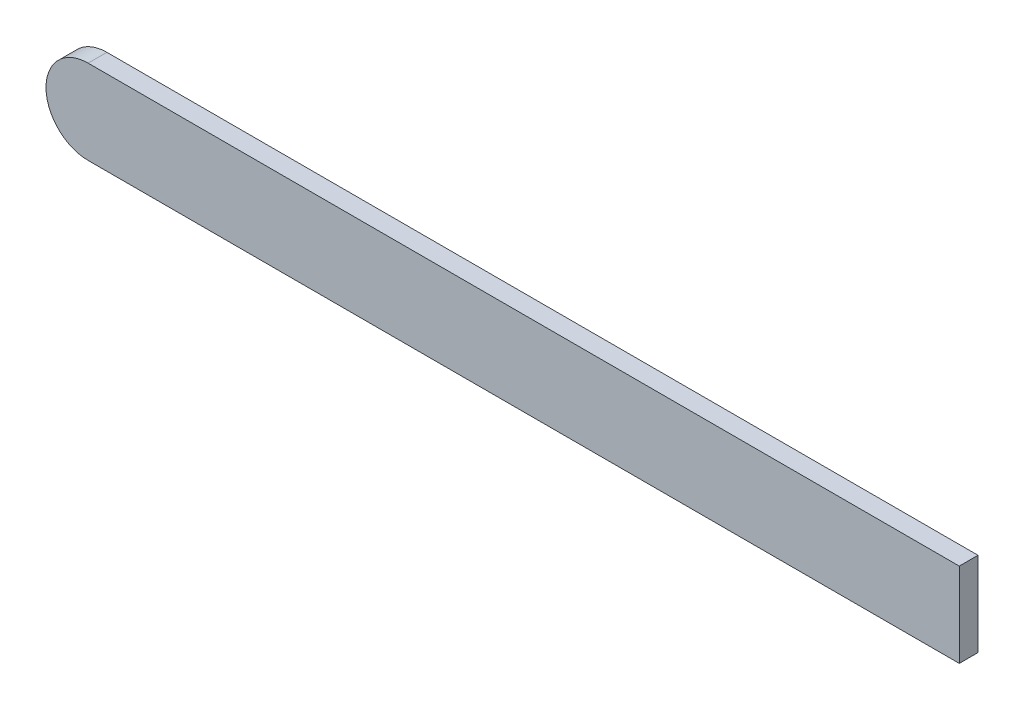
SolidWorks part; units mm, degrees
ref_plane "Front Plane" through (0, 0, 0) normal (0, 0, 1) x (1, 0, 0)
ref_plane "Top Plane" through (0, 0, 0) normal (0, 1, 0) x (1, 0, 0)
ref_plane "Right Plane" through (0, 0, 0) normal (1, 0, 0) x (0, 0, -1)
sketch "Sketch1" plane through (0, 0, 0) normal (0, 0, 1) x (1, 0, 0)
  line L0 (-44.45, 0) -> (50.0074, 0) construction
  line L1 (-44.45, 4.7625) -> (53.975, 4.7625)
  line L2 (-44.45, -4.7625) -> (53.975, -4.7625)
  line L3 (53.975, 4.7625) -> (53.975, -4.7625)
  arc A0 (-44.45, 4.7625) -> (-44.45, -4.7625) centre (-44.45, 0) ccw
  point P3 (0, 0)
  point P8 (0, 0)
  point P9 (0, 0)
  dimension "D2" = 4.7625
  dimension "D1" = 98.425
  dimension "D3" = 4.7625
  dimension "D4" = 53.975
  dimension "D5" = 9.525
extrude "Boss-Extrude1" add sketch "Sketch1" along normal blind 2.1167
